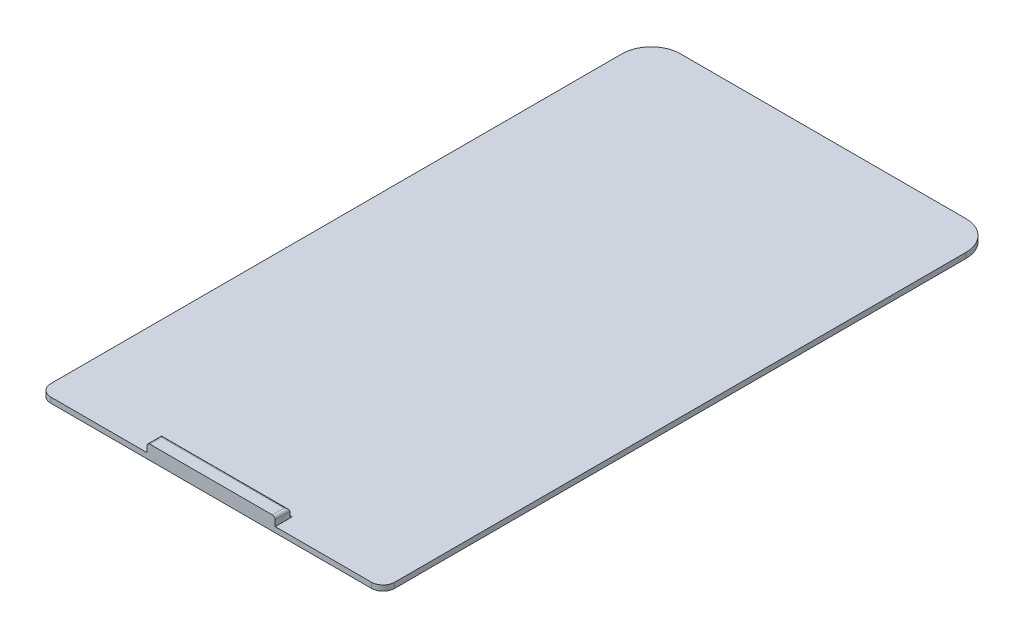
SolidWorks part; units mm, degrees
ref_plane "Front Plane" through (0, 0, 0) normal (0, 0, 1) x (1, 0, 0)
ref_plane "Top Plane" through (0, 0, 0) normal (0, 1, 0) x (1, 0, 0)
ref_plane "Right Plane" through (0, 0, 0) normal (1, 0, 0) x (0, 0, -1)
sketch "Sketch2" plane through (0, 0, 0) normal (0, 1, 0) x (1, 0, 0)
  line L1 (-59, 105) -> (0, 105)
  line L2 (-59, 105) -> (-59, 0)
  line L3 (-59, 0) -> (0, 0)
  line L4 (0, 105) -> (0, 0)
  dimension "D1" = 59
  dimension "D2" = 105
extrude "Boss-Extrude1" add sketch "Sketch2" along normal blind 0.925
sketch "Sketch3" plane through (0, 0.925, 0) normal (0, 1, 0) x (1, 0, 0)
  line L0 (-59, 0) -> (0, 0) construction
  line L1 (-40.5, 2.5) -> (-18.5, 2.5)
  line L2 (-40.5, 2.5) -> (-40.5, 0)
  line L3 (-40.5, 0) -> (-18.5, 0)
  line L4 (-18.5, 2.5) -> (-18.5, 0)
  point P6 (-29.5, 0)
  point P7 (-29.5, 2.5)
  dimension "D1" = 2.5
  dimension "D2" = 22
extrude "Boss-Extrude2" add sketch "Sketch3" along normal blind 1.5
fillet "Fillet1" radius 0.5 4 edges at (-40.5, 2.425, -1.25) (-29.5, 0.925, -2.5) (-29.5, 2.425, -2.5) (-18.5, 2.425, -1.25)
fillet "Fillet2" radius 2 2 edges at (-59, 0.4625, 0) (0, 0.4625, 0)
fillet "Fillet3" radius 5 2 edges at (-59, 0.4625, -105) (0, 0.4625, -105)
